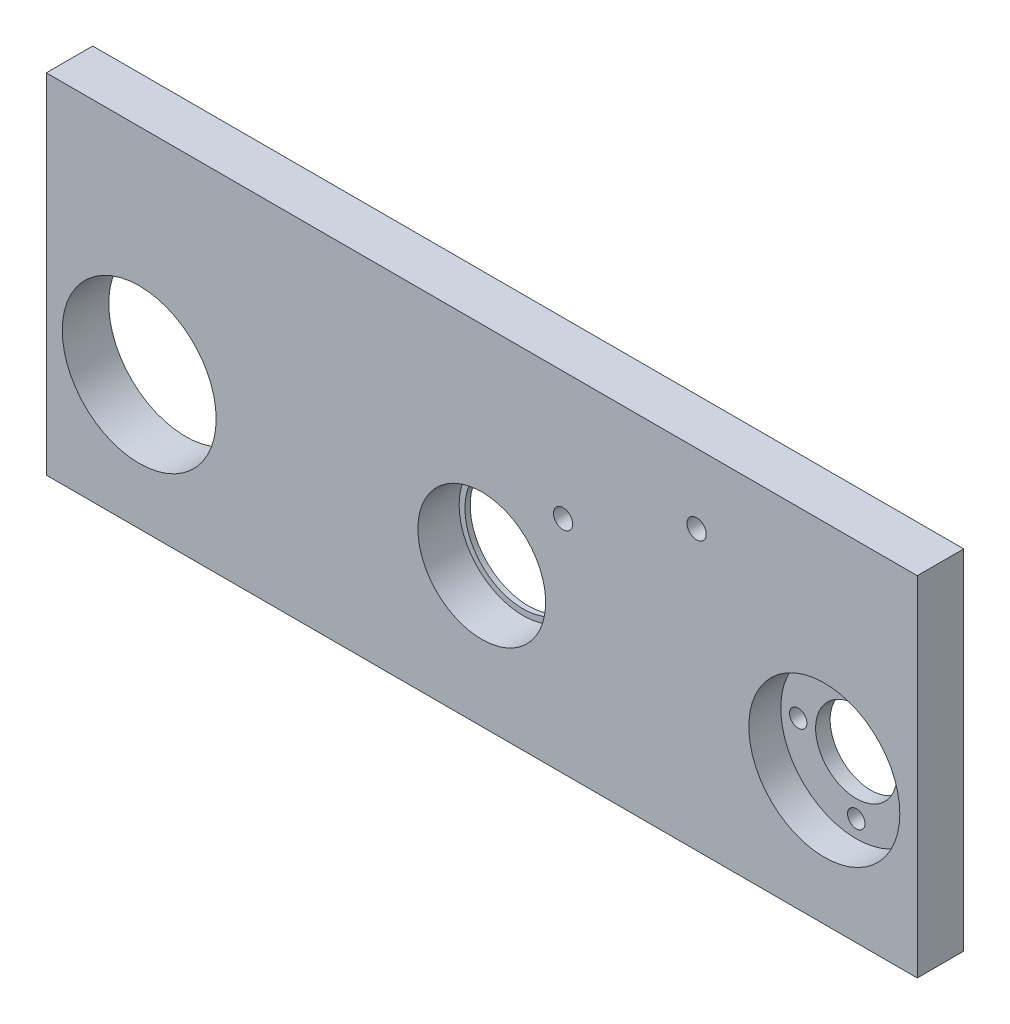
SolidWorks part; units mm, degrees
ref_plane "Front" through (0, 0, 0) normal (0, 0, 1) x (1, 0, 0)
ref_plane "Top" through (0, 0, 0) normal (0, 1, 0) x (1, 0, 0)
ref_plane "Right" through (0, 0, 0) normal (1, 0, 0) x (0, 0, -1)
sketch "Esquisse1" plane through (0, 0, 0) normal (0, 0, 1) x (1, 0, 0)
  line L1 (0, 0) -> (150, 0)
  line L2 (0, 0) -> (0, 60)
  line L3 (0, 60) -> (150, 60)
  line L4 (150, 0) -> (150, 60)
  dimension "D1" = 150
  dimension "D2" = 60
extrude "Boss.-Extru.1" add sketch "Esquisse1" along normal blind 8
sketch "Esquisse2" plane through (0, 0, 8) normal (0, 0, 1) x (1, 0, 0)
  line L0 (75, 0) -> (75, 24) construction
  line L1 (0, 0) -> (150, 0) construction
  circle A0 centre (75, 24) radius 11
  dimension "D1" = 22
  dimension "D2" = 24
extrude "Enlèv. mat.-Extru.1" cut sketch "Esquisse2" against normal blind 7.1 and the other way through all
sketch "Esquisse3" plane through (0, 0, 0.9) normal (0, 0, 1) x (1, 0, 0)
  circle A0 centre (75, 24) radius 10
  dimension "D1" = 20
extrude "Enlèv. mat.-Extru.2" cut sketch "Esquisse3" against normal through all
sketch "Esquisse4" plane through (0, 0, 8) normal (0, 0, 1) x (1, 0, 0)
  line L0 (133.9915, 23) -> (75, 24) construction
  line L1 (0, 0) -> (150, 0) construction
  circle A0 centre (133.9915, 23) radius 7
  dimension "D2" = 23
  dimension "D3" = 14
  dimension "D1" = 59
extrude "Enlèv. mat.-Extru.3" cut sketch "Esquisse4" against normal through all
sketch "Esquisse5" plane through (0, 0, 8) normal (0, 0, 1) x (1, 0, 0)
  circle A0 centre (133.9915, 23) radius 13
  dimension "D1" = 26
extrude "Enlèv. mat.-Extru.4" cut sketch "Esquisse5" against normal blind 5.5
sketch "Esquisse6" plane through (0, 0, 8) normal (0, 0, 1) x (1, 0, 0)
  line L0 (75, 0) -> (75, 60) construction
  line L1 (0, 0) -> (150, 0) construction
  line L2 (150, 60) -> (0, 60) construction
  line L3 (75, 24) -> (16.0085, 23) construction
  line L4 (133.9915, 23) -> (75, 23) construction
  line L5 (75, 23) -> (16.0085, 23) construction
  circle A0 centre (16.0085, 23) radius 13.25
  dimension "D2" = 26.5
  dimension "D1" = 59
extrude "Enlèv. mat.-Extru.5" cut sketch "Esquisse6" against normal through all both and the other way through all
sketch "Esquisse7" plane through (0, 0, 8) normal (0, 0, 1) x (1, 0, 0)
  line L0 (75, 24) -> (89, 24) construction
  line L1 (89, 24) -> (89, 38) construction
  circle A0 centre (89, 38) radius 1.65
  circle A1 centre (112, 48) radius 1.65
  dimension "D1" = 3.3
  dimension "D4" = 23
  dimension "D5" = 10
  dimension "D2" = 14
  dimension "D3" = 14
extrude "Enlèv. mat.-Extru.6" cut sketch "Esquisse7" against normal through all both and the other way through all
sketch "Esquisse8" plane through (0, 0, 2.5) normal (0, 0, 1) x (1, 0, 0)
  line L0 (133.9915, 23) -> (133.9915, 13) construction
  circle A0 centre (133.9915, 13) radius 1.5
  circle A1 centre (123.9915, 23) radius 1.5
  circle A2 centre (133.9915, 33) radius 1.5
  circle A3 centre (143.9915, 23) radius 1.5
  point P4 (122.2243, 24.7112)
  point P5 (133.9915, 23)
  point P12 (133.9915, 23)
  dimension "D1" = 3
  dimension "D2" = 10
  dimension "D3" = 4
extrude "Enlèv. mat.-Extru.7" cut sketch "Esquisse8" against normal through all both and the other way through all
